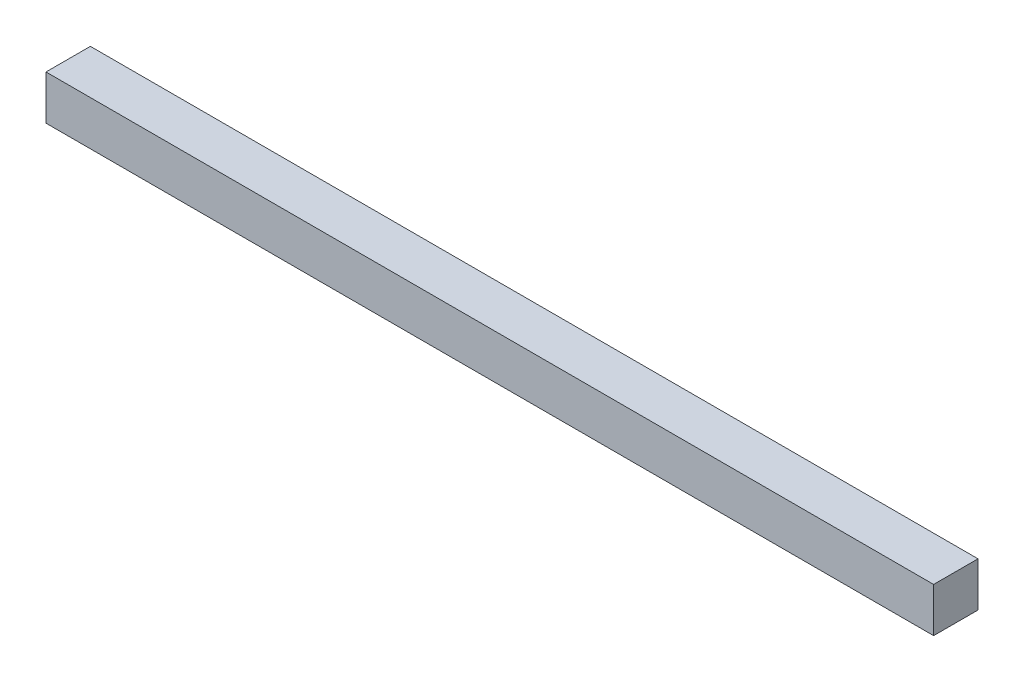
SolidWorks part; units mm, degrees
material "Acrylic (Medium-high impact)"
ref_plane "Front Plane" through (0, 0, 0) normal (0, 0, 1) x (1, 0, 0)
ref_plane "Top Plane" through (0, 0, 0) normal (0, 1, 0) x (1, 0, 0)
ref_plane "Right Plane" through (0, 0, 0) normal (1, 0, 0) x (0, 0, -1)
sketch "Sketch1" plane through (0, 0, 0) normal (0, 0, 1) x (1, 0, 0)
  line L1 (-100, -5) -> (100, -5)
  line L2 (-100, -5) -> (-100, 5)
  line L3 (-100, 5) -> (100, 5)
  line L4 (100, -5) -> (100, 5)
  line L5 (-100, -5) -> (100, 5) construction
  line L6 (-100, 5) -> (100, -5) construction
  point P0 (0, 0)
  dimension "D1" = 200
  dimension "D2" = 10
extrude "Boss-Extrude1" add sketch "Sketch1" along normal blind 10
